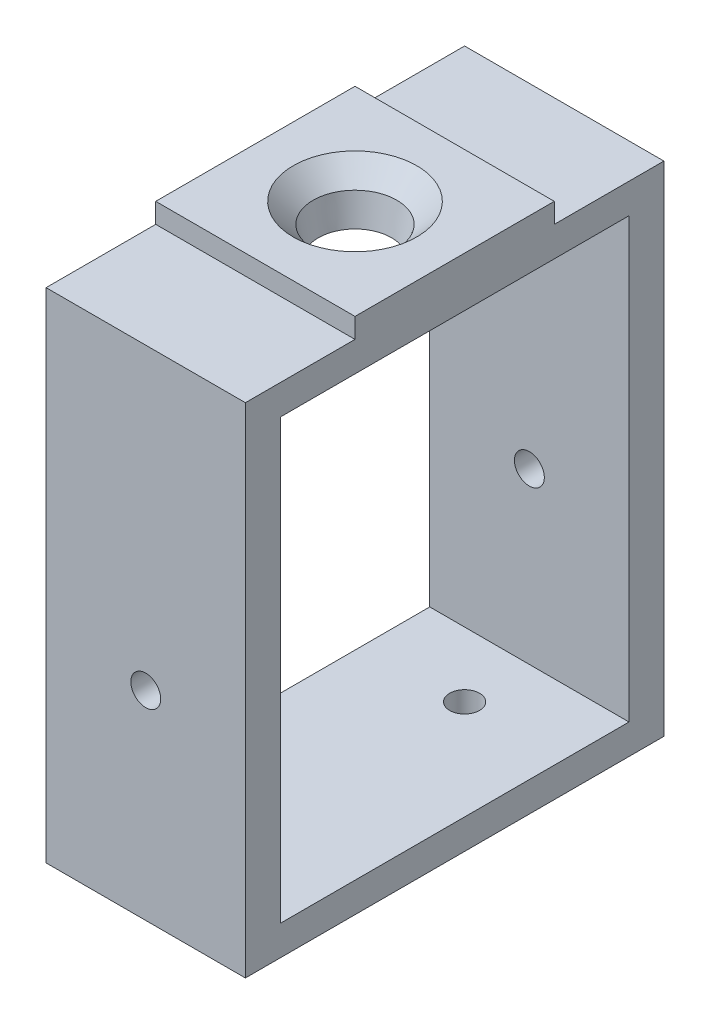
SolidWorks part; units mm, degrees
ref_plane "前视基准面" through (0, 0, 0) normal (0, 0, 1) x (1, 0, 0)
ref_plane "上视基准面" through (0, 0, 0) normal (0, 1, 0) x (1, 0, 0)
ref_plane "右视基准面" through (0, 0, 0) normal (1, 0, 0) x (0, 0, -1)
sketch "草图1" plane through (0, 0, 0) normal (0, 1, 0) x (1, 0, 0)
  line L1 (0, 0) -> (20, 0)
  line L2 (0, 0) -> (0, -42)
  line L3 (0, -42) -> (20, -42)
  line L4 (20, 0) -> (20, -42)
  dimension "D1" = 20
  dimension "D2" = 42
extrude "凸台-拉伸1" add sketch "草图1" along normal blind 3
sketch "草图2" plane through (0, 3, 0) normal (0, 1, 0) x (1, 0, 0)
  line L0 (20, -42) -> (20, 0) construction
  line L1 (0, -42) -> (20, -42)
  line L2 (0, -42) -> (0, -38.5)
  line L3 (0, -38.5) -> (20, -38.5)
  line L4 (20, -42) -> (20, -38.5)
  line L5 (0, 0) -> (0, -42) construction
  line L6 (20, 0) -> (0, 0)
  line L7 (20, 0) -> (20, -3.5)
  line L8 (20, -3.5) -> (0, -3.5)
  line L9 (0, 0) -> (0, -3.5)
  dimension "D1" = 3.5
  dimension "D2" = 3.5
extrude "凸台-拉伸2" add sketch "草图2" along normal blind 47
sketch "草图3" plane through (0, 0, 42) normal (0, 0, 1) x (1, 0, 0)
  line L0 (0, 0) -> (20, 0) construction
  circle A0 centre (10, 20) radius 1.5
  dimension "D1" = 3
  dimension "D2" = 20
extrude "切除-拉伸1" cut sketch "草图3" against normal through all
sketch "草图4" plane through (20, 0, 0) normal (1, 0, 0) x (0, 0, -1)
  line L0 (-3.5, 50) -> (-3.5, 3) construction
  line L1 (-38.5, 50) -> (-3.5, 50)
  line L2 (-38.5, 50) -> (-38.5, 47)
  line L3 (-38.5, 47) -> (-3.5, 47)
  line L4 (-3.5, 50) -> (-3.5, 47)
  dimension "D1" = 3
extrude "凸台-拉伸3" add sketch "草图4" against normal blind 20
sketch "草图8" plane through (0, 50, 0) normal (0, 1, 0) x (1, 0, 0)
  line L0 (0, 0) -> (0, -42) construction
  line L1 (0, -31) -> (20, -31)
  line L2 (0, -31) -> (0, -11)
  line L3 (0, -11) -> (20, -11)
  line L4 (20, -31) -> (20, -11)
  line L5 (20, -42) -> (20, 0) construction
  line L6 (0, -42) -> (20, -42) construction
  dimension "D1" = 20
  dimension "D2" = 11
extrude "凸台-拉伸5" add sketch "草图8" along normal blind 2
sketch "草图9" plane through (0, 52, 0) normal (0, 1, 0) x (1, 0, 0)
  circle A0 centre (10, -21) radius 6.2
  dimension "D1" = 12.4
extrude "切除-拉伸4" cut sketch "草图9" against normal blind 2 draft 45
sketch "草图10" plane through (0, 50, 0) normal (0, 1, 0) x (1, 0, 0)
  circle A0 centre (10, -21) radius 4.2
extrude "切除-拉伸5" cut sketch "草图10" against normal blind 3 draft 10
sketch "草图11" plane through (0, 0, 0) normal (0, -1, 0) x (-1, 0, 0)
  line L0 (0, -42) -> (-20, -42) construction
  line L1 (-20, 0) -> (0, 0) construction
  circle A0 centre (-10, -32) radius 1.5
  circle A1 centre (-10, -10) radius 1.5
  dimension "D1" = 3
  dimension "D2" = 3
  dimension "D3" = 10
  dimension "D4" = 10
extrude "切除-拉伸6" cut sketch "草图11" against normal blind 3
